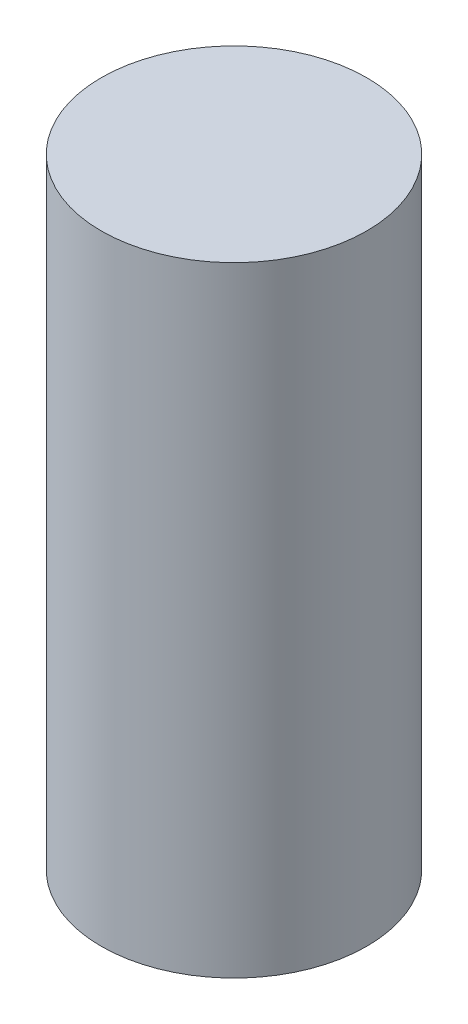
SolidWorks part; units mm, degrees
ref_plane "Front Plane" through (0, 0, 0) normal (0, 0, 1) x (1, 0, 0)
ref_plane "Top Plane" through (0, 0, 0) normal (0, 1, 0) x (1, 0, 0)
ref_plane "Right Plane" through (0, 0, 0) normal (1, 0, 0) x (0, 0, -1)
other "Configuration Table"
sketch "Sketch1" plane through (0, 0, 0) normal (0, 1, 0) x (1, 0, 0)
  circle A0 centre (650, 770) radius 6
extrude "TOPPING_ayar_mil_4" add sketch "Sketch1" along normal blind 28 from offset 12 separate body
